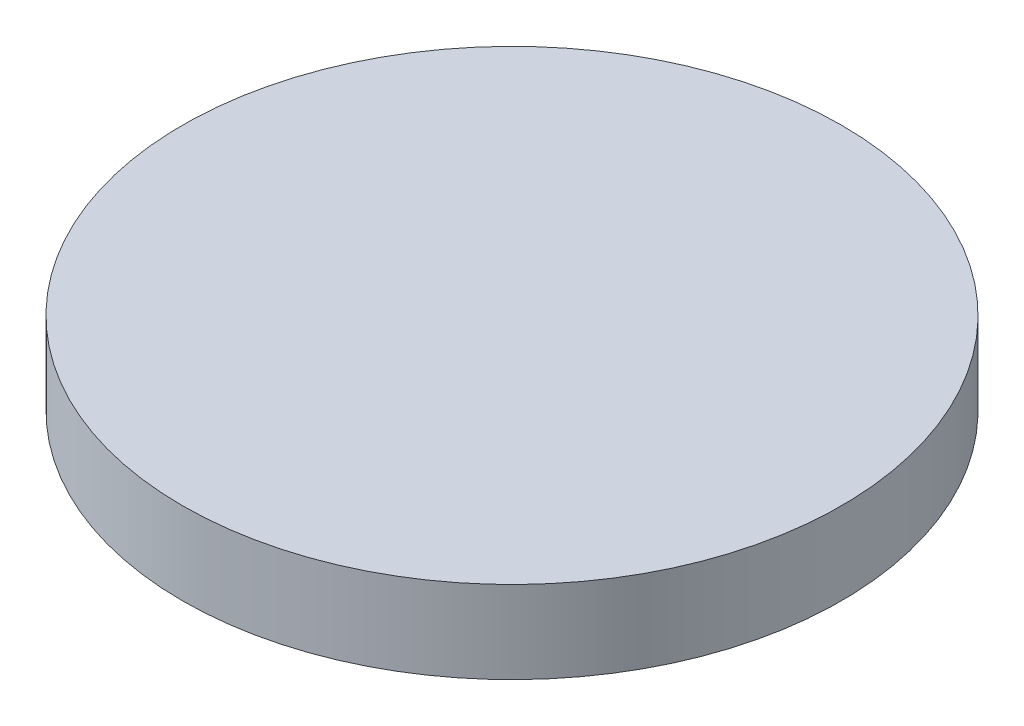
SolidWorks part; units mm, degrees
material "6061 Alloy"
ref_plane "Front Plane" through (0, 0, 0) normal (0, 0, 1) x (1, 0, 0)
ref_plane "Top Plane" through (0, 0, 0) normal (0, 1, 0) x (1, 0, 0)
ref_plane "Right Plane" through (0, 0, 0) normal (1, 0, 0) x (0, 0, -1)
sketch "Sketch3" plane through (0, 0, 0) normal (0, 1, 0) x (1, 0, 0)
  circle A0 centre (0, 0) radius 50.8
  dimension "D1" = 101.6
extrude "Boss-Extrude1" add sketch "Sketch3" along normal blind 12.7
